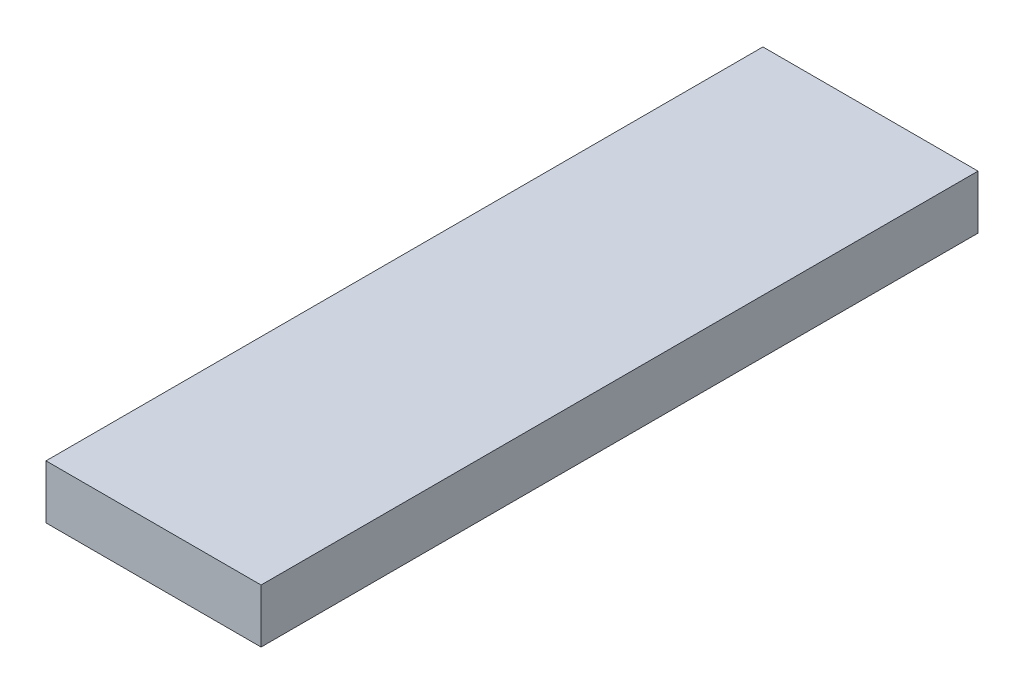
SolidWorks part; units mm, degrees
material "99.5% Aluminum Oxide (2)"
ref_plane "Front" through (0, 0, 0) normal (0, 0, 1) x (1, 0, 0)
ref_plane "Top" through (0, 0, 0) normal (0, 1, 0) x (1, 0, 0)
ref_plane "Right" through (0, 0, 0) normal (1, 0, 0) x (0, 0, -1)
sketch "Sketch1" plane through (0, 0, 0) normal (0, 1, 0) x (1, 0, 0)
  line L1 (0, 50) -> (30, 50)
  line L2 (0, 50) -> (0, -50)
  line L3 (0, -50) -> (30, -50)
  line L4 (30, 50) -> (30, -50)
  dimension "D1" = 100
  dimension "D2" = 30
extrude "Boss-Extrude1" add sketch "Sketch1" along normal mid plane 7.5
sketch "Sketch2" plane through (0, 3.75, 0) normal (0, 1, 0) x (1, 0, 0)
  line L0 (0, 50) -> (0, -50) construction
  line L1 (0, 25) -> (15, 25)
  line L2 (0, 25) -> (0, -25)
  line L3 (0, -25) -> (15, -25)
  line L4 (15, 25) -> (15, -25)
  dimension "D1" = 50
  dimension "D2" = 15
extrude "Cut-Extrude1" cut sketch "Sketch2" against normal blind 4 from offset 3
